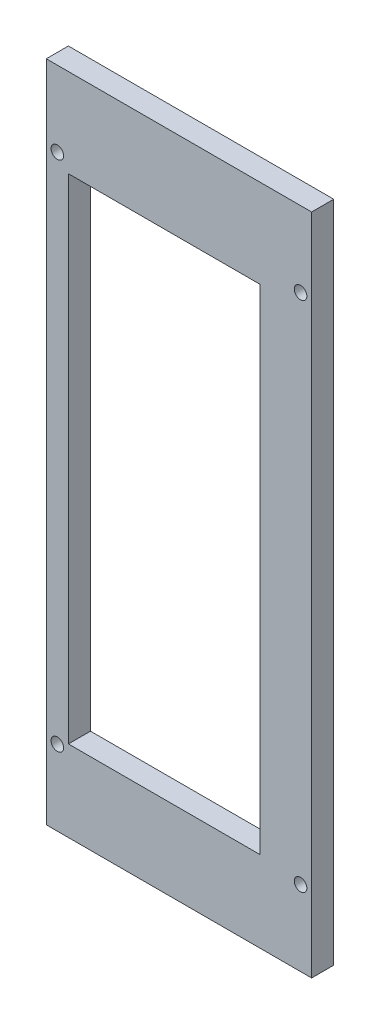
SolidWorks part; units mm, degrees
ref_plane "Front Plane" through (0, 0, 0) normal (0, 0, 1) x (1, 0, 0)
ref_plane "Top Plane" through (0, 0, 0) normal (0, 1, 0) x (1, 0, 0)
ref_plane "Right Plane" through (0, 0, 0) normal (1, 0, 0) x (0, 0, -1)
sketch "Sketch1" plane through (0, 0, 0) normal (0, 0, 1) x (1, 0, 0)
  line L0 (18, -82.0031) -> (18, -17.0031) construction
  line L2 (0, 0) -> (0, -102.0061)
  line L4 (36, 0) -> (36, -102.0061)
  line L5 (32, -6.0031) -> (36, -6.0031)
  line L6 (0, 0) -> (0, 18.809) construction
  line L7 (36, -6.0031) -> (36, -10.0031)
  line L8 (0, -10.0031) -> (0, 0)
  line L9 (4, -96.0031) -> (32, -96.0031)
  line L10 (0, -10.0031) -> (0, 0)
  line L11 (0, -6.0031) -> (0, -10.0031)
  line L12 (36, -10.0031) -> (36, 0)
  line L13 (4, -6.0031) -> (0, -6.0031)
  line L14 (36, -10.0031) -> (36, 0)
  line L15 (4, -96.0031) -> (32, -96.0031)
  line L16 (33, -18.0031) -> (3, -18.0031)
  line L17 (3, -18.0031) -> (3, -85.0031)
  line L18 (3, -85.0031) -> (33, -85.0031)
  line L19 (33, -18.0031) -> (33, -85.0031)
  line L20 (0, -51.0031) -> (36, -51.0031) construction
  line L21 (4, -96.0031) -> (0, -96.0031)
  line L22 (4, -92.0031) -> (4, -89.5031) construction
  line L23 (0, -96.0031) -> (0, -92.0031)
  line L24 (36, -92.0031) -> (36, -102.0061)
  line L25 (36, -96.0031) -> (36, -92.0031)
  line L26 (36, -92.0031) -> (36, -102.0061)
  line L27 (0, -92.0031) -> (0, -102.0061)
  line L28 (32, -96.0031) -> (36, -96.0031)
  line L29 (0, -92.0031) -> (0, -102.0061)
  line L31 (4, -6.0031) -> (32, -6.0031)
  arc A1 (4, -6.0031) -> (0, -10.0031) centre (4, -10.0031) ccw construction
  arc A2 (32, -6.0031) -> (36, -10.0031) centre (32, -10.0031) cw construction
  arc A5 (32, -96.0031) -> (36, -92.0031) centre (32, -92.0031) ccw construction
  arc A6 (4, -96.0031) -> (0, -92.0031) centre (4, -92.0031) cw construction
  arc A7 (32, -96.0031) -> (36, -92.0031) centre (32, -92.0031) ccw construction
  arc A8 (4, -96.0031) -> (0, -92.0031) centre (4, -92.0031) cw construction
  point P25 (18, -85.0031)
  point P26 (18, -18.0031)
  dimension "D2" = 12
  dimension "D3" = 4
  dimension "D1" = 36
  dimension "D4" = 90
  dimension "D6" = 3
  dimension "D9" = 67
extrude "Boss-Extrude1" add sketch "Sketch1" along normal blind 3
sketch "Sketch3" plane through (0, 0, 0) normal (0, 0, -1) x (-1, 0, 0)
  line L0 (-33, -18.0031) -> (-33, -16.2246) construction
  line L1 (-33, -16.2246) -> (-36, -16.2246) construction
  line L2 (-36, -6.0031) -> (-36, -96.0031) construction
  line L3 (-18, -18.0031) -> (-18, -6.0031) construction
  line L4 (-33, -18.0031) -> (-3, -18.0031) construction
  line L5 (0, -6.0031) -> (-36, -6.0031) construction
  line L6 (-3, -16.2246) -> (0, -16.2246) construction
  line L7 (-36, -51.0031) -> (0, -51.0031) construction
  line L8 (0, -6.0031) -> (0, -96.0031) construction
  line L9 (-3, -85.7815) -> (0, -85.7815) construction
  line L10 (-18, -84.0031) -> (-18, -96.0031) construction
  line L11 (-33, -85.7815) -> (-36, -85.7815) construction
  line L12 (-33, -84.0031) -> (-33, -85.7815) construction
  circle A0 centre (-34.5, -16.2246) radius 0.85
  circle A1 centre (-1.5, -16.2246) radius 0.85
  circle A2 centre (-1.5, -85.7815) radius 0.85
  circle A3 centre (-34.5, -85.7815) radius 0.85
  dimension "D1" = 1.7
extrude "Cut-Extrude1" cut sketch "Sketch3" against normal up to surface (3 mm away) up to face at (18, -51.0031, 3)
sketch "Sketch4" plane through (0, 0, 3) normal (0, 0, 1) x (1, 0, 0)
  line L0 (3, -85.0031) -> (33, -85.0031) construction
  line L1 (33, -18.0031) -> (29, -18.0031)
  line L2 (33, -18.0031) -> (33, -85.0031)
  line L3 (33, -85.0031) -> (29, -85.0031)
  line L4 (29, -18.0031) -> (29, -85.0031)
  dimension "D1" = 4
extrude "Boss-Extrude2" add sketch "Sketch4" against normal up to surface (3 mm away) up to face at (35.35, -85.7815, 0)
